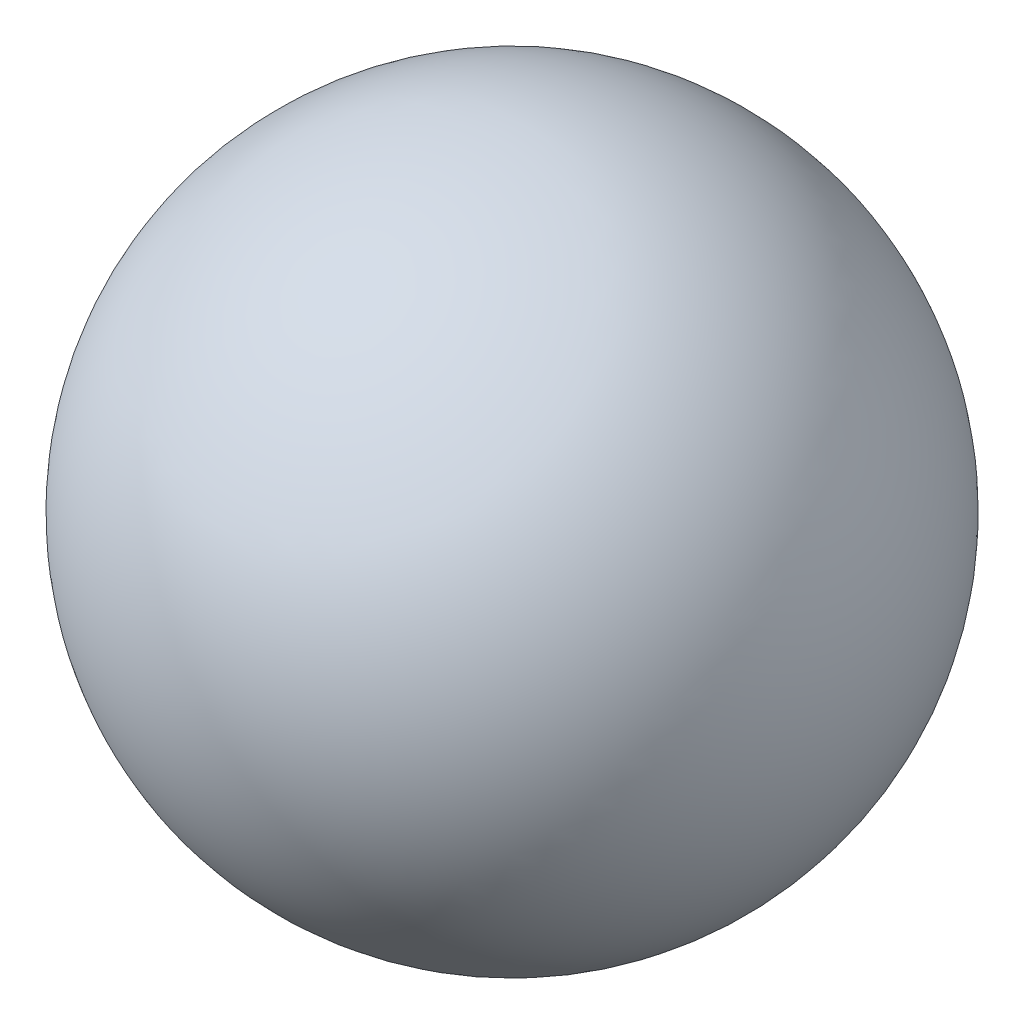
SolidWorks part; units mm, degrees
ref_plane "Front Plane" through (0, 0, 0) normal (0, 0, 1) x (1, 0, 0)
ref_plane "Top Plane" through (0, 0, 0) normal (0, 1, 0) x (1, 0, 0)
ref_plane "Right Plane" through (0, 0, 0) normal (1, 0, 0) x (0, 0, -1)
sketch "Sketch1" plane through (0, 0, 0) normal (0, 1, 0) x (1, 0, 0)
  line L0 (0, -43.053) -> (0, 43.053)
  arc A0 (0, -43.053) -> (0, 43.053) centre (0, 0) ccw
  dimension "D1" = 86.106
revolve "Revolve1" add sketch "Sketch1" angle 360 about L0
